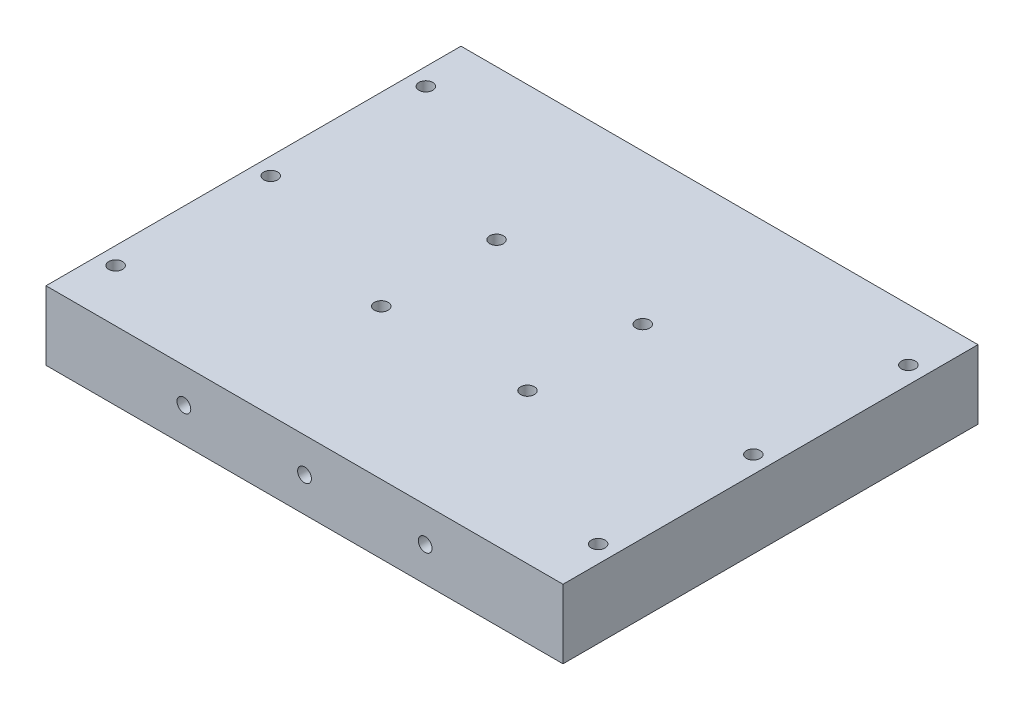
SolidWorks part; units mm, degrees
material "Oak"
ref_plane "Front Plane" through (0, 0, 0) normal (0, 0, 1) x (1, 0, 0)
ref_plane "Top Plane" through (0, 0, 0) normal (0, 1, 0) x (1, 0, 0)
ref_plane "Right Plane" through (0, 0, 0) normal (1, 0, 0) x (0, 0, -1)
sketch "Sketch1" plane through (0, 0, 0) normal (0, 1, 0) x (1, 0, 0)
  line L1 (0, 0) -> (150, 0)
  line L2 (0, 0) -> (0, 120.4)
  line L3 (0, 120.4) -> (150, 120.4)
  line L4 (150, 0) -> (150, 120.4)
  dimension "D1" = 120.4
  dimension "D2" = 150
extrude "Boss-Extrude2" add sketch "Sketch1" along normal blind 20
sketch "Szkic1" plane through (0, 20, 0) normal (0, 1, 0) x (1, 0, 0)
  line L0 (75, 0) -> (75, 120.4) construction
  line L1 (0, 0) -> (150, 0) construction
  line L2 (150, 120.4) -> (0, 120.4) construction
  line L3 (0, 60.2) -> (150, 60.2) construction
  line L4 (0, 120.4) -> (0, 0) construction
  line L5 (150, 0) -> (150, 120.4) construction
  line L7 (75, 60.2) -> (100, 60.2) construction
  line L8 (100, 60.2) -> (50, 60.2) construction
  line L9 (50, 60.2) -> (50, 80.2) construction
  line L10 (50, 80.2) -> (100, 80.2) construction
  line L11 (100, 80.2) -> (100, 40.2) construction
  line L12 (100, 40.2) -> (50, 40.2) construction
  line L13 (50, 40.2) -> (50, 60.2) construction
  line L14 (50, 40.2) -> (53.79, 40.2) construction
  line L15 (53.79, 40.2) -> (53.79, 43.48) construction
  line L16 (100, 40.2) -> (96.21, 40.2) construction
  line L17 (96.21, 40.2) -> (96.21, 43.48) construction
  line L18 (100, 80.2) -> (96.21, 80.2) construction
  line L19 (96.21, 80.2) -> (96.21, 76.92) construction
  line L20 (50, 80.2) -> (53.79, 80.2) construction
  line L21 (53.79, 80.2) -> (53.79, 76.92) construction
  circle A4 centre (53.79, 76.92) radius 2
  circle A5 centre (96.21, 76.92) radius 2
  circle A6 centre (53.79, 43.48) radius 2
  circle A7 centre (96.21, 43.48) radius 2
  point P6 (75.0117, 60.195)
sketch "Szkic4" plane through (0, 0, -120.4) normal (0, 0, -1) x (-1, 0, 0)
  line L0 (0, 10) -> (-40, 10) construction
  line L1 (0, 20) -> (0, 0) construction
  line L2 (-40, 10) -> (-75, 10) construction
  line L3 (-75, 10) -> (-110, 10) construction
  circle A0 centre (-40, 10) radius 2
  circle A1 centre (-75, 10) radius 2
  circle A2 centre (-110, 10) radius 2
extrude "Wytnij-wyciągnięcie2" cut sketch "Szkic4" against normal blind 10
sketch "Szkic5" plane through (0, 0, 0) normal (0, 0, 1) x (1, 0, 0)
  line L0 (0, 10) -> (40, 10) construction
  line L1 (0, 20) -> (0, 0) construction
  line L2 (40, 10) -> (75, 10) construction
  line L3 (75, 10) -> (110, 10) construction
  circle A0 centre (40, 10) radius 2
  circle A1 centre (75, 10) radius 2
  circle A2 centre (110, 10) radius 2
extrude "Wytnij-wyciągnięcie3" cut sketch "Szkic5" against normal blind 10
sketch "Szkic6" plane through (0, 20, 0) normal (0, 1, 0) x (1, 0, 0)
  line L0 (0, 0) -> (5, 0) construction
  line L1 (0, 0) -> (150, 0) construction
  line L2 (5, 0) -> (5, 120.4) construction
  line L3 (150, 120.4) -> (0, 120.4) construction
  line L4 (0, 15.2) -> (5, 15.2) construction
  line L5 (150, 0) -> (145, 0) construction
  line L6 (145, 0) -> (145, 15.2) construction
  line L7 (145, 15.2) -> (145, 60.2) construction
  line L8 (145, 60.2) -> (145, 105.2) construction
  line L9 (0, 120.4) -> (0, 0) construction
  circle A3 centre (145, 105.2) radius 2
  circle A4 centre (145, 60.2) radius 2
  circle A5 centre (145, 15.2) radius 2
  circle A6 centre (5, 15.2) radius 2
  circle A7 centre (5, 60.2) radius 2
  circle A8 centre (5, 105.2) radius 2
extrude "Wytnij-wyciągnięcie5" cut sketch "Szkic1" against normal blind 10
extrude "Wytnij-wyciągnięcie6" cut sketch "Szkic6" against normal blind 20
